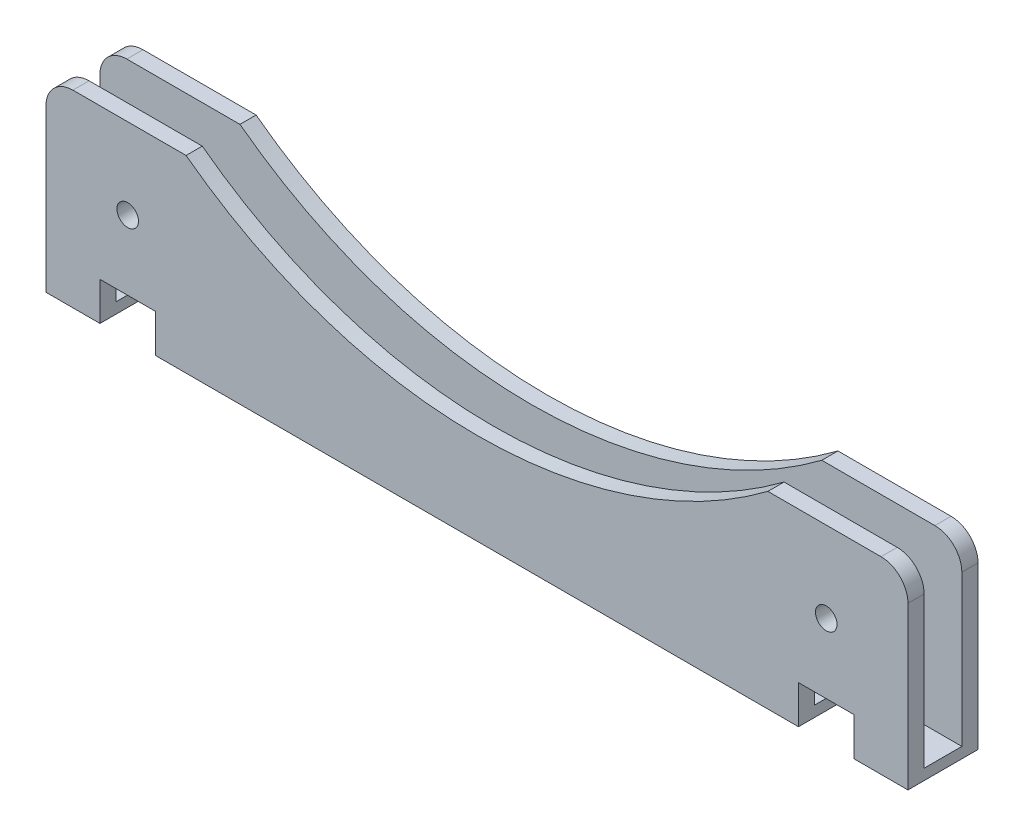
SolidWorks part; units mm, degrees
ref_plane "前视基准面" through (0, 0, 0) normal (0, 0, 1) x (1, 0, 0)
ref_plane "上视基准面" through (0, 0, 0) normal (0, 1, 0) x (1, 0, 0)
ref_plane "右视基准面" through (0, 0, 0) normal (1, 0, 0) x (0, 0, -1)
sketch "草图1" plane through (0, 0, 0) normal (0, 0, 1) x (1, 0, 0)
  line L0 (0, 0) -> (0, -148.0216) construction
  line L1 (54, -72) -> (75, -72)
  line L2 (-75, -72) -> (-54, -72)
  line L3 (-80, -77) -> (-80, -107)
  line L4 (-80, -107) -> (80, -107)
  line L5 (80, -77) -> (80, -107)
  circle A0 centre (0, 0) radius 100 construction
  circle A1 centre (64.8325, -87) radius 8.5 construction
  circle A2 centre (-64.8325, -87) radius 8.5 construction
  circle A3 centre (-64.8325, -87) radius 2
  circle A4 centre (64.8325, -87) radius 2
  arc A5 (-54, -72) -> (54, -72) centre (0, 0) ccw
  arc A6 (75, -72) -> (80, -77) centre (75, -77) cw
  arc A7 (-75, -72) -> (-80, -77) centre (-75, -77) ccw
  point P18 (80, -72)
  dimension "D1" = 200
  dimension "D2" = 17
  dimension "D5" = 4
  dimension "D6" = 4
  dimension "D7" = 107
  dimension "D9" = 180
  dimension "D10" = 5
  dimension "D3" = 20
  dimension "D4" = 160
  dimension "D8" = 35
extrude "凸台-拉伸1" add sketch "草图1" along normal blind 13
sketch "草图2" plane through (80, 0, 0) normal (1, 0, 0) x (0, 0, -1)
  line L0 (-6.5, -72) -> (-6.5, -50072) construction
  line L1 (-13, -72) -> (0, -72) construction
  line L2 (-13, -107) -> (-13, -77) construction
  line L3 (-10, -70.1586) -> (-3, -70.1586)
  line L4 (-10, -70.1586) -> (-10, -105)
  line L5 (-10, -105) -> (-3, -105)
  line L6 (-3, -70.1586) -> (-3, -105)
  line L7 (0, -77) -> (0, -72) construction
  line L8 (-13, -107) -> (0, -107) construction
  point P4 (-6.5, -72)
  dimension "D1" = 3
  dimension "D2" = 3
  dimension "D3" = 2
  dimension "D4" = 7
extrude "切除-拉伸1" cut sketch "草图2" against normal through all
sketch "草图3" plane through (0, 0, 13) normal (0, 0, 1) x (1, 0, 0)
  line L0 (0, -107) -> (0, 49893) construction
  line L1 (-69.9825, -107) -> (-59.6825, -107)
  line L2 (-69.9825, -107) -> (-69.9825, -99.9)
  line L3 (-69.9825, -99.9) -> (-59.6825, -99.9)
  line L4 (-59.6825, -107) -> (-59.6825, -99.9)
  line L5 (-80, -107) -> (80, -107) construction
  line L6 (-64.8325, -87) -> (-64.8325, -120.5701) construction
  line L7 (-69.9825, -107) -> (-69.9825, -99.9)
  line L8 (-59.6825, -107) -> (-59.6825, -99.9)
  line L9 (-69.9825, -107) -> (-69.9825, -99.9)
  line L10 (-59.6825, -107) -> (-59.6825, -99.9)
  line L11 (-69.9825, -107) -> (-69.9825, -99.9)
  line L12 (-59.6825, -107) -> (-59.6825, -99.9)
  line L13 (69.9825, -107) -> (59.6825, -107)
  line L14 (59.6825, -107) -> (59.6825, -99.9)
  line L15 (69.9825, -99.9) -> (59.6825, -99.9)
  line L16 (69.9825, -107) -> (69.9825, -99.9)
  point P9 (0, -107)
  line M9 (-80, -107) -> (80, -107)
  dimension "D1" = 7.1
  dimension "D2" = 10.3
extrude "切除-拉伸2" cut sketch "草图3" against normal blind 60 contours L4 L3 L2 M9 | L16 L15 L14 M9
